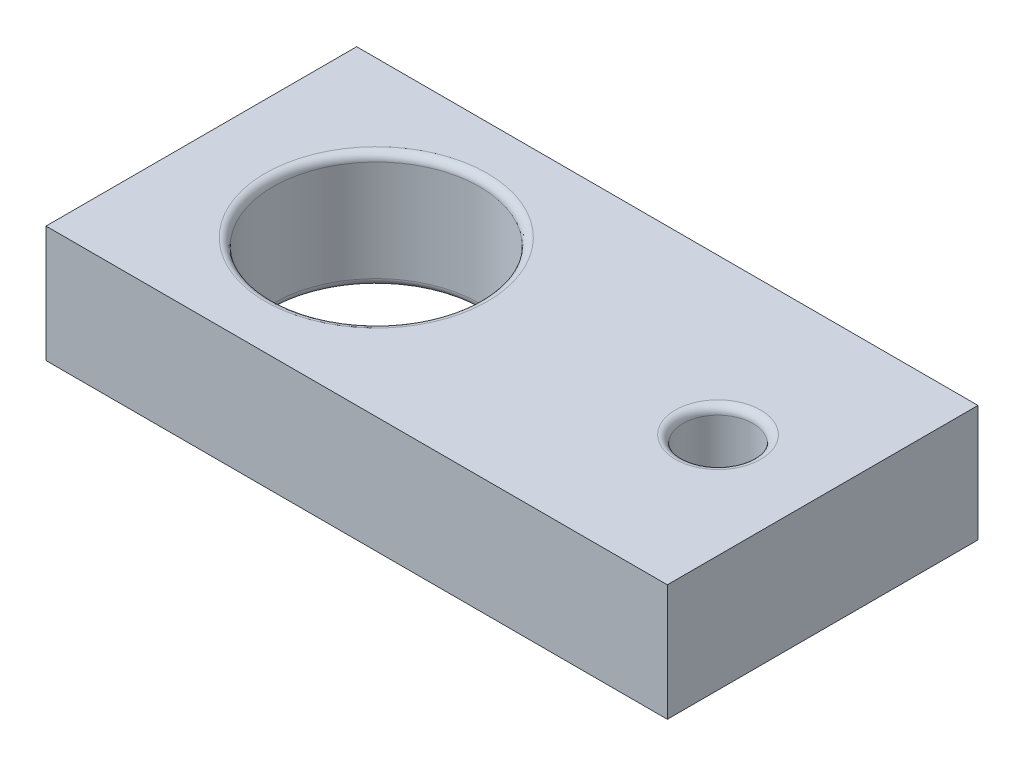
SolidWorks part; units mm, degrees
ref_plane "前基準面" through (0, 0, 0) normal (0, 0, 1) x (1, 0, 0)
ref_plane "上基準面" through (0, 0, 0) normal (0, 1, 0) x (1, 0, 0)
ref_plane "右基準面" through (0, 0, 0) normal (1, 0, 0) x (0, 0, -1)
sketch "草圖1" plane through (0, 0, 0) normal (0, 1, 0) x (1, 0, 0)
  line L1 (0, 0) -> (125, 0)
  line L2 (0, 0) -> (0, 40)
  line L3 (0, 40) -> (125, 40)
  line L4 (125, 0) -> (125, 40)
  dimension "D1" = 125
  dimension "D2" = 40
extrude "填料-伸長1" add sketch "草圖1" along normal blind 15
sketch "草圖2" plane through (0, 15, 0) normal (0, 1, 0) x (1, 0, 0)
  line L0 (-4.3311, 20) -> (135.7424, 20) construction
  line L1 (0, 0) -> (125, 0) construction
  line L2 (125, 40) -> (0, 40) construction
  line L3 (0, 40) -> (0, 0) construction
  circle A0 centre (18.5267, 20) radius 8.9
  circle A1 centre (106.5267, 20) radius 4.5
  circle A2 centre (62.5267, 20) radius 13.3
  dimension "D1" = 26.6
  dimension "D2" = 9
  dimension "D3" = 17.8
  dimension "D4" = 44
  dimension "D5" = 44
  dimension "D6" = 18.5267
extrude "除料-伸長1" cut sketch "草圖2" against normal through all
chamfer "導角1" distance 1 angle 45 1 edges at (18.5267, 15, -11.1)
chamfer "導角2" distance 1 angle 45 1 edges at (18.5267, 0, -11.1)
fillet "圓角1" radius 1 4 edges at (62.5267, 0, -6.7) (106.5267, 0, -15.5) (106.5267, 15, -15.5) (62.5267, 15, -6.7)
sketch "草圖3" plane through (0, 15, 0) normal (0, 1, 0) x (1, 0, 0)
  line L2 (0, 0) -> (40, 0)
  line L3 (0, 0) -> (0, 61.183)
  line L4 (0, 61.183) -> (40, 61.183)
  line L5 (40, 0) -> (40, 61.183)
  dimension "D1" = 40
extrude "除料-伸長2" cut sketch "草圖3" against normal through all
sketch "草圖5" plane through (0, 15, 0) normal (0, 1, 0) x (1, 0, 0)
  line L1 (125, 0) -> (120, 0)
  line L2 (125, 0) -> (125, 48.3848)
  line L3 (125, 48.3848) -> (120, 48.3848)
  line L4 (120, 0) -> (120, 48.3848)
  dimension "D1" = 5
extrude "除料-伸長3" cut sketch "草圖5" against normal through all
